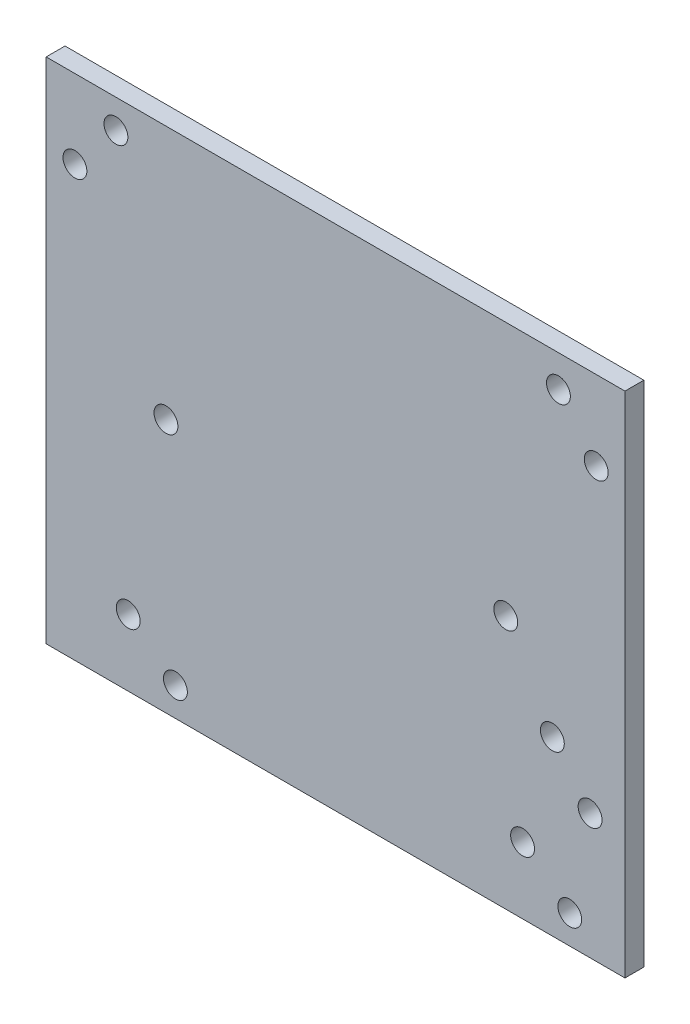
SolidWorks part; units mm, degrees
ref_plane "Front Plane" through (0, 0, 0) normal (0, 0, 1) x (1, 0, 0)
ref_plane "Top Plane" through (0, 0, 0) normal (0, 1, 0) x (1, 0, 0)
ref_plane "Right Plane" through (0, 0, 0) normal (1, 0, 0) x (0, 0, -1)
sketch "Sketch1" plane through (0, 0, 0) normal (0, 0, 1) x (1, 0, 0)
  line L0 (959.4886, 308.695) -> (959.4886, 257.3944) construction
  line L1 (959.4886, 234.6614) -> (959.4886, 406.5207) construction
  line L2 (862.0448, 217.2783) -> (1056.7178, 217.2783)
  line L3 (862.0448, 217.2783) -> (862.0448, 388.2332)
  line L4 (862.0448, 388.2332) -> (1056.7178, 388.2332)
  line L5 (1056.7178, 217.2783) -> (1056.7178, 388.2332)
  line L6 (902.3386, 302.7557) -> (1016.6386, 302.7557) construction
  circle A0 centre (1022.28, 239.6533) radius 2.5273 construction
  circle A1 centre (1038.155, 226.9533) radius 2.5273 construction
  circle A2 centre (889.6448, 239.6533) radius 2.5273 construction
  circle A3 centre (1034.3339, 377.4809) radius 2.5273 construction
  circle A4 centre (1047.0428, 361.6131) radius 2.5273 construction
  circle A5 centre (871.7198, 361.7933) radius 2.5273 construction
  circle A6 centre (885.5053, 378.5582) radius 2.5273 construction
  circle A7 centre (1022.28, 239.6533) radius 2.5273 construction
  circle A8 centre (1038.155, 226.9533) radius 2.5273 construction
  circle A9 centre (889.6448, 239.6533) radius 2.5273 construction
  circle A10 centre (1034.3339, 377.4809) radius 2.5273 construction
  circle A11 centre (1047.0428, 361.6131) radius 2.5273 construction
  circle A12 centre (871.7198, 361.7933) radius 2.5273 construction
  circle A13 centre (885.5053, 378.5582) radius 2.5273 construction
  circle A14 centre (905.5198, 226.9533) radius 2.5273 construction
  circle A15 centre (905.5198, 226.9533) radius 2.5273 construction
  circle A16 centre (1022.28, 239.6533) radius 4.0127
  circle A17 centre (1038.155, 226.9533) radius 4.0127
  circle A18 centre (889.6448, 239.6533) radius 4.0127
  circle A19 centre (1034.3339, 377.4809) radius 4.0127
  circle A20 centre (1047.0428, 361.6131) radius 4.0127
  circle A21 centre (871.7198, 361.7933) radius 4.0127
  circle A22 centre (885.5053, 378.5582) radius 4.0127
  circle A23 centre (905.5198, 226.9533) radius 4.0127
  circle A24 centre (885.5053, 378.5582) radius 6.5 construction
  circle A25 centre (871.7198, 361.7933) radius 6.5 construction
  circle A26 centre (889.6448, 239.6533) radius 6.5 construction
  circle A27 centre (905.5198, 226.9533) radius 6.5 construction
  circle A28 centre (1022.28, 239.6533) radius 6.5 construction
  circle A29 centre (1038.155, 226.9533) radius 6.5 construction
  circle A30 centre (1047.0428, 361.6131) radius 6.5 construction
  circle A31 centre (1034.3339, 377.4809) radius 6.5 construction
  circle A32 centre (-682.1218, 370.9328) radius 4.0127 construction
  circle A33 centre (902.3386, 302.7557) radius 4.0127
  circle A34 centre (-672.6612, 269.9726) radius 4.0132 construction
  circle A35 centre (-672.6612, 269.9726) radius 4.0132 construction
  circle A36 centre (1016.6386, 302.7557) radius 4.0127
  circle A37 centre (1044.9866, 259.4145) radius 2.5273 construction
  circle A38 centre (1032.2866, 275.2895) radius 2.5273 construction
  circle A39 centre (1044.9866, 259.4145) radius 2.5273 construction
  circle A40 centre (1032.2866, 275.2895) radius 2.5273 construction
  circle A41 centre (1032.2866, 275.2895) radius 4.0254
  circle A42 centre (1044.9866, 259.4145) radius 4.0254
  point P60 (959.4886, 302.7557)
  point P76 (862.0448, 302.7557)
  dimension "D2" = 114.3
  dimension "D1" = 13
  dimension "D3" = 3.175
  dimension "D4" = 3.175
  dimension "D5" = 3.175
  dimension "D6" = 3.175
  dimension "D7" = 8.0508
extrude "Boss-Extrude1" add sketch "Sketch1" along normal blind 6.35
move or copy body "Body-Move/Copy1" bodies to move or copy 103 parameters "D1"=0, "D2"=0, "D3"=0
